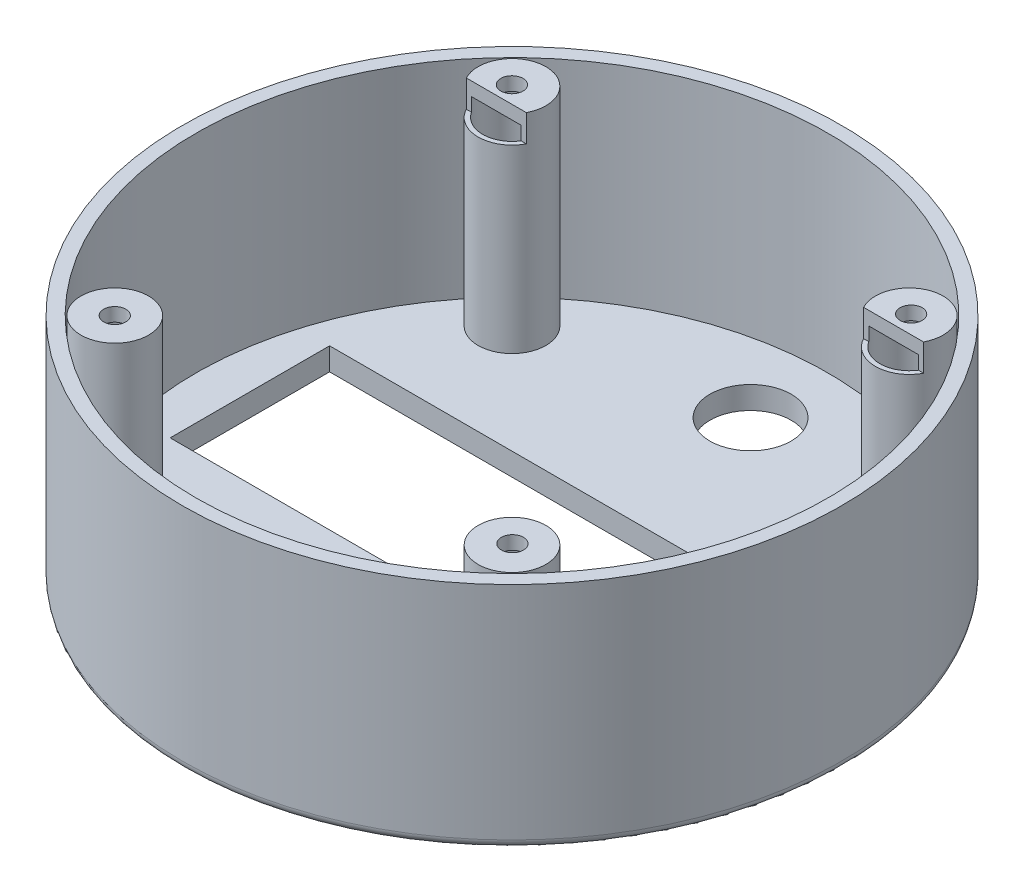
SolidWorks part; units mm, degrees
ref_plane "Front Plane" through (0, 0, 0) normal (0, 0, 1) x (1, 0, 0)
ref_plane "Top Plane" through (0, 0, 0) normal (0, 1, 0) x (1, 0, 0)
ref_plane "Right Plane" through (0, 0, 0) normal (1, 0, 0) x (0, 0, -1)
sketch "Sketch2" plane through (0, 0, 0) normal (0, 1, 0) x (1, 0, 0)
  circle A0 centre (0, 0) radius 36.5
extrude "Boss-Extrude1" add sketch "Sketch2" along normal blind 2.5
sketch "Sketch3" plane through (0, 2.5, 0) normal (0, 1, 0) x (1, 0, 0)
  circle A0 centre (0, 0) radius 36.5
  circle A1 centre (0, 0) radius 35
extrude "Boss-Extrude2" add sketch "Sketch3" along normal blind 35
sketch "Sketch4" plane through (0, 2.5, 0) normal (0, 1, 0) x (1, 0, 0)
  line L7 (-22, 22) -> (22, -22) construction
  line L8 (-22, -22) -> (22, 22) construction
  circle A0 centre (-22, 22) radius 3.75
  circle A1 centre (22, 22) radius 3.75
  circle A2 centre (22, -22) radius 3.75
  circle A3 centre (-22, -22) radius 3.75
extrude "Boss-Extrude3" add sketch "Sketch4" along normal blind 35
sketch "Sketch5" plane through (0, 37.5, 0) normal (0, 1, 0) x (1, 0, 0)
  line L5 (22, -22) -> (-22, 22) construction
  line L6 (22, 22) -> (-22, -22) construction
  circle A0 centre (-22, -22) radius 1.225
  circle A1 centre (-22.145, 22.1354) radius 1.225
  circle A2 centre (21.9598, 22.2466) radius 1.225
  circle A3 centre (21.9042, -21.8582) radius 1.225
  point P0 (0, 0)
extrude "Cut-Extrude2" cut sketch "Sketch5" against normal through all
sketch "Sketch9" plane through (0, 0, 0) normal (0, -1, 0) x (1, 0, 0)
  line L1 (-22, 22) -> (22, 22)
  line L2 (-22, 22) -> (-22, -22)
  line L3 (-22, -22) -> (22, -22)
  line L4 (22, 22) -> (22, -22)
  line L5 (-22, 22) -> (22, -22) construction
  line L6 (-22, -22) -> (22, 22) construction
  circle A0 centre (22, 22) radius 3.25
  circle A1 centre (22, -22) radius 3.25
  circle A2 centre (-22, -22) radius 3.25
  circle A3 centre (-22, 22) radius 3.25
  point P0 (0, 0)
  circle M1 centre (-22.145, -22.1354) radius 1.225
  circle M2 centre (21.9598, -22.2466) radius 1.225
  circle M3 centre (21.9042, 21.8582) radius 1.225
  circle M4 centre (-22, 22) radius 1.225
extrude "Cut-Extrude7" cut sketch "Sketch9" against normal blind 24 contours L4 A0 L1 M3 | L1 A0 L4 M3 | L3 A1 L4 M2 | L4 A1 L3 M2 | L2 A2 L3 M1 | L1 A3 L2 M4 | L2 A3 L1 M4 | L3 A2 L2 M1
fillet "Fillet2" radius 0.75 1 edges at (0, 37.5, 35)
sketch "Sketch17" plane through (0, 0, 0) normal (0, -1, 0) x (1, 0, 0)
  circle A1 centre (0, -26.419) radius 4.5
  point P2 (0, 0)
extrude "Cut-Extrude9" cut sketch "Sketch17" against normal blind 10
sketch "Sketch19" plane through (0, 0, 0) normal (0, -1, 0) x (1, 0, 0)
  line L8 (30.2475, -9.9947) -> (-30.201, -9.9947)
  line L9 (30.2475, -9.9947) -> (30.2475, 7.6653)
  line L10 (30.2475, 7.6653) -> (-30.201, 7.6653)
  line L11 (-30.201, -9.9947) -> (-30.201, 7.6653)
  line L12 (30.2475, -9.9947) -> (-30.201, 7.6653) construction
  line L13 (30.2475, 7.6653) -> (-30.201, -9.9947) construction
extrude "Cut-Extrude10" cut sketch "Sketch19" against normal blind 10
fillet "Fillet7" radius 1 1 edges at (0, 0, 36.5)
sketch "Sketch20" plane through (0, 37.5, 0) normal (0, 1, 0) x (1, 0, 0)
  circle A0 centre (0, 0) radius 36.5
extrude "Cut-Extrude11" cut sketch "Sketch20" against normal blind 12
sketch "Sketch21" plane through (0, 25.5, 0) normal (0, 1, 0) x (1, 0, 0)
  line L0 (25.322, 20.2601) -> (-25.322, 20.2601)
  line L1 (-25.322, 20.2601) -> (-25.322, 17.7047)
  line L2 (-25.322, 17.7047) -> (25.322, 17.7047)
  line L3 (25.322, 17.7047) -> (25.322, 20.2601)
  circle A0 centre (22, 22) radius 3.75 construction
  circle A1 centre (-22, 22) radius 3.75 construction
extrude "Cut-Extrude13" cut sketch "Sketch21" against normal blind 3
